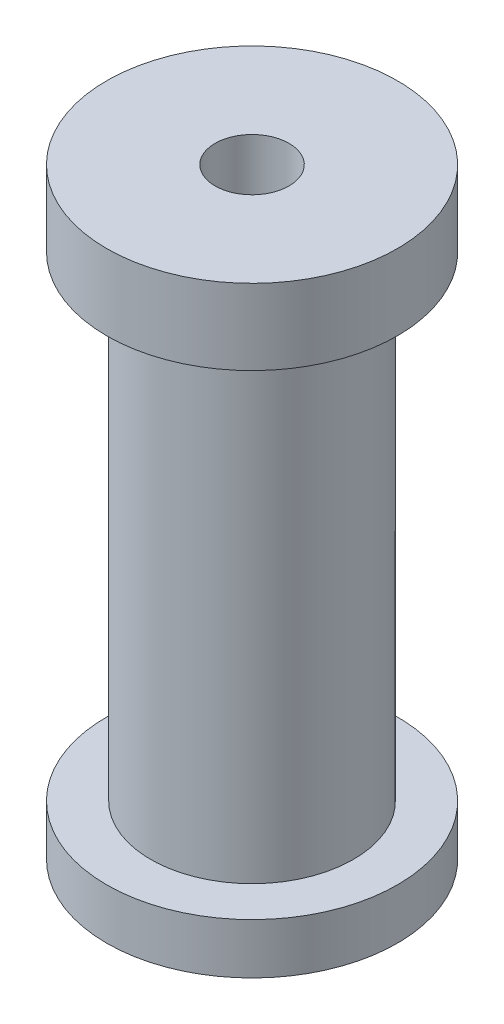
SolidWorks part; units mm, degrees
ref_plane "Front Plane" through (0, 0, 0) normal (0, 0, 1) x (1, 0, 0)
ref_plane "Top Plane" through (0, 0, 0) normal (0, 1, 0) x (1, 0, 0)
ref_plane "Right Plane" through (0, 0, 0) normal (1, 0, 0) x (0, 0, -1)
sketch "Sketch1" plane through (0, 0, 0) normal (0, 1, 0) x (1, 0, 0)
  circle A0 centre (0, 0) radius 13.4366
  dimension "D1" = 26.8732
extrude "Boss-Extrude1" add sketch "Sketch1" along normal blind 4.6736
sketch "Sketch2" plane through (0, 4.6736, 0) normal (0, 1, 0) x (1, 0, 0)
  circle A0 centre (0, 0) radius 9.3726
  dimension "D1" = 18.7452
extrude "Boss-Extrude2" add sketch "Sketch2" along normal blind 43.942
sketch "Sketch3" plane through (0, 48.6156, 0) normal (0, 1, 0) x (1, 0, 0)
  circle A0 centre (0, 0) radius 13.4366
  circle A1 centre (0, 0) radius 13.4366 construction
extrude "Boss-Extrude3" add sketch "Sketch3" along normal blind 6.985
sketch "Sketch4" plane through (0, 0, 0) normal (0, -1, 0) x (1, 0, 0)
  circle A0 centre (0, 0) radius 3.4163
  dimension "D1" = 6.8326
extrude "Cut-Extrude1" cut sketch "Sketch4" against normal through all
